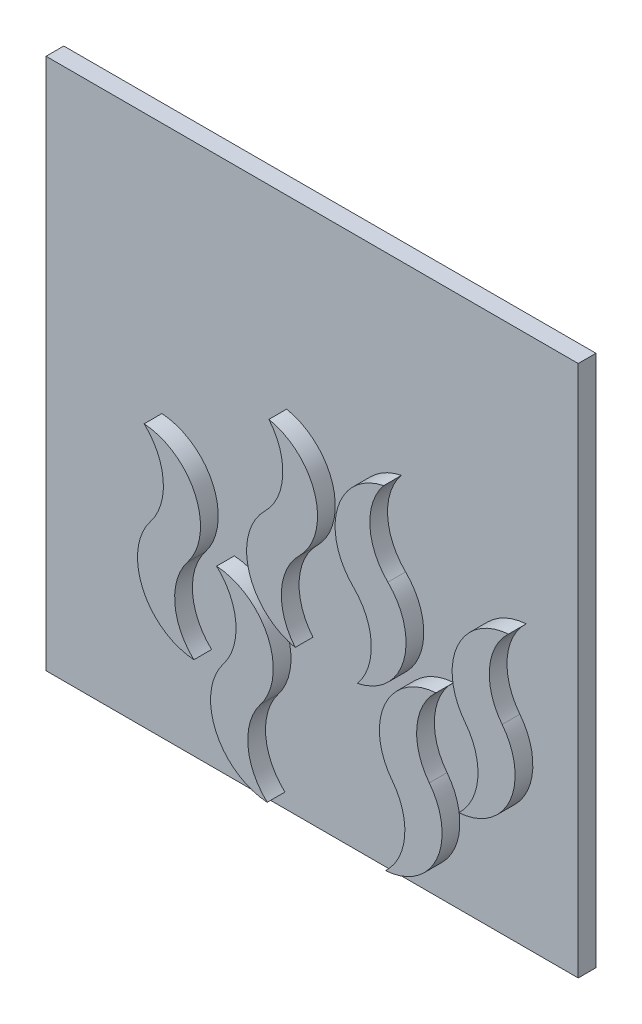
SolidWorks part; units mm, degrees
material "Obyčejná uhlíková ocel"
ref_plane "Přední rovina" through (0, 0, 0) normal (0, 0, 1) x (1, 0, 0)
ref_plane "Horní rovina" through (0, 0, 0) normal (0, 1, 0) x (1, 0, 0)
ref_plane "Pravá rovina" through (0, 0, 0) normal (1, 0, 0) x (0, 0, -1)
sketch "Skica1" plane through (0, 0, 0) normal (0, 0, 1) x (1, 0, 0)
  line L1 (0, 0) -> (300, 0)
  line L2 (0, 0) -> (0, 300)
  line L3 (0, 300) -> (300, 300)
  line L4 (300, 0) -> (300, 300)
  dimension "D1" = 300
extrude "Přidat vysunutím1" add sketch "Skica1" along normal blind 10
sketch "Skica3" plane through (0, 0, 10) normal (0, 0, 1) x (1, 0, 0)
  line L0 (68.8884, 112.3393) -> (89.7636, 102.9262) construction
  line L2 (65.3238, 158.2311) -> (93.3281, 57.0345) construction
  line L3 (109.9481, 63.2834) -> (130.8716, 53.9782) construction
  line L4 (106.1467, 109.1561) -> (134.673, 8.1054) construction
  line L5 (133.3078, 149.5887) -> (152.805, 137.5788) construction
  line L6 (135.6518, 195.559) -> (150.4609, 91.6085) construction
  line L7 (168, 17.0415) -> (168, 212.0807) construction
  line L9 (0, 300) -> (0, 0) construction
  arc A71 (68.8884, 112.3393) -> (93.3281, 57.0345) centre (95.8154, 91.1861) ccw
  arc A72 (68.8884, 112.3393) -> (65.3238, 158.2311) centre (42.1472, 133.3466) ccw
  arc A73 (89.7636, 102.9262) -> (93.3281, 57.0345) centre (116.5047, 81.919) ccw
  arc A74 (89.7636, 102.9262) -> (65.3238, 158.2311) centre (62.8366, 124.0795) ccw
  arc A75 (109.9481, 63.2834) -> (134.673, 8.1054) centre (136.9839, 42.2694) ccw
  arc A76 (109.9481, 63.2834) -> (106.1467, 109.1561) centre (83.0988, 84.1523) ccw
  arc A77 (130.8716, 53.9782) -> (134.673, 8.1054) centre (157.7208, 33.1092) ccw
  arc A78 (130.8716, 53.9782) -> (106.1467, 109.1561) centre (103.8358, 74.9921) ccw
  arc A79 (133.3078, 149.5887) -> (150.4609, 91.6085) centre (157.3029, 125.1601) ccw
  arc A80 (133.3078, 149.5887) -> (135.6518, 195.559) centre (109.4782, 173.8487) ccw
  arc A81 (152.805, 137.5788) -> (150.4609, 91.6085) centre (176.6345, 113.3188) ccw
  arc A82 (152.805, 137.5788) -> (135.6518, 195.559) centre (128.8098, 162.0074) ccw
  arc A83 (246.2364, 102.9262) -> (270.6762, 158.2311) centre (273.1634, 124.0795) cw
  arc A84 (267.1116, 112.3393) -> (270.6762, 158.2311) centre (293.8528, 133.3466) cw
  arc A85 (267.1116, 112.3393) -> (242.6719, 57.0345) centre (240.1846, 91.1861) cw
  arc A86 (246.2364, 102.9262) -> (242.6719, 57.0345) centre (219.4953, 81.919) cw
  arc A87 (226.0519, 63.2834) -> (201.327, 8.1054) centre (199.0161, 42.2694) cw
  arc A88 (205.1284, 53.9782) -> (201.327, 8.1054) centre (178.2792, 33.1092) cw
  arc A89 (205.1284, 53.9782) -> (229.8533, 109.1561) centre (232.1642, 74.9921) cw
  arc A90 (226.0519, 63.2834) -> (229.8533, 109.1561) centre (252.9012, 84.1523) cw
  arc A91 (202.6922, 149.5887) -> (185.5391, 91.6085) centre (178.6971, 125.1601) cw
  arc A92 (183.195, 137.5788) -> (185.5391, 91.6085) centre (159.3655, 113.3188) cw
  arc A93 (183.195, 137.5788) -> (200.3482, 195.559) centre (207.1902, 162.0074) cw
  arc A94 (202.6922, 149.5887) -> (200.3482, 195.559) centre (226.5218, 173.8487) cw
  point P1 (79.326, 107.6328)
  point P18 (120.4098, 58.6308)
  point P26 (103.8358, 109.2342)
  point P29 (143.0564, 143.5838)
  point P31 (62.8366, 158.3215)
  point P38 (128.8098, 196.2495)
  dimension "D1" = 34.0058
  dimension "D2" = 8.8042
  dimension "D3" = 46.03
  dimension "D12" = 105
  dimension "D5" = 34.0058
  dimension "D9" = 34.0058
  dimension "D4" = 105
  dimension "D6" = 8.8042
  dimension "D7" = 46.03
  dimension "D8" = 105
  dimension "D10" = 8.8042
  dimension "D11" = 46.03
  dimension "D13" = 168
extrude "Přidat vysunutím3" add sketch "Skica3" along normal blind 10
